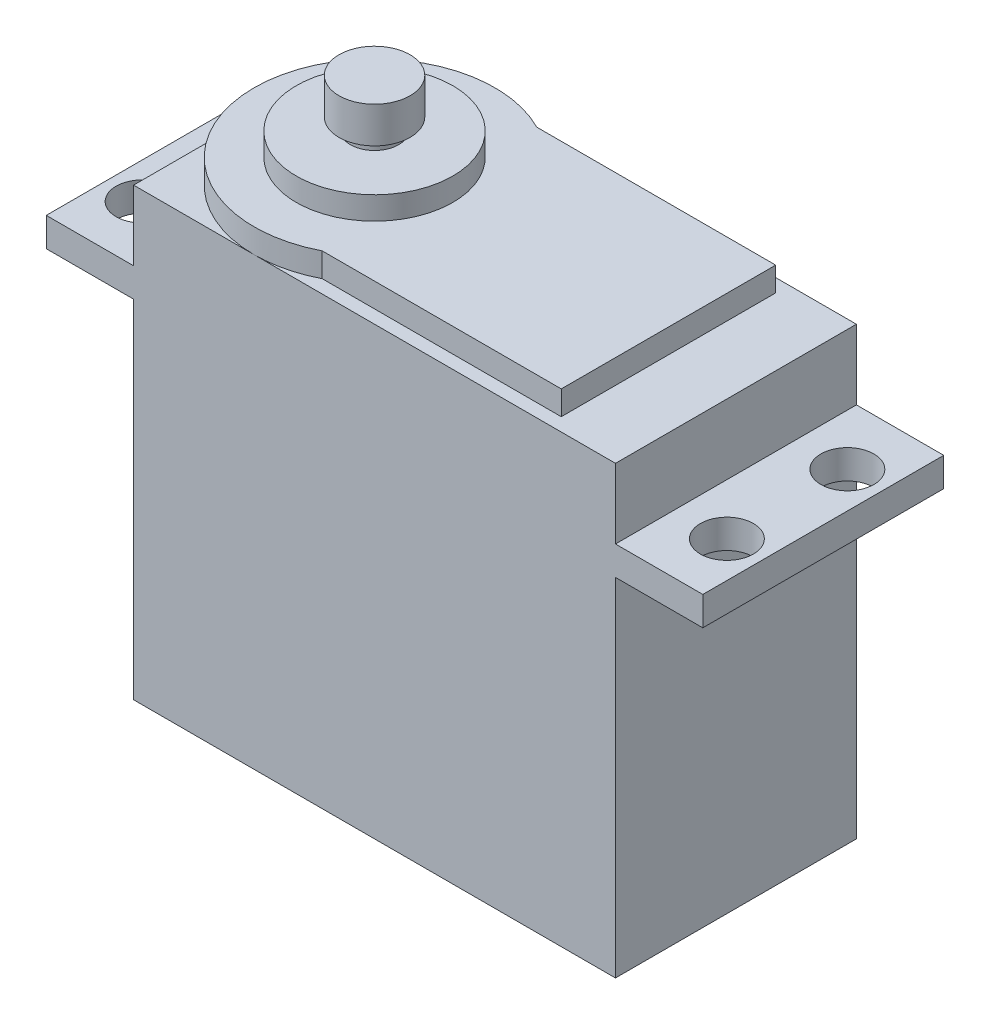
SolidWorks part; units mm, degrees
ref_plane "前视基准面" through (0, 0, 0) normal (0, 0, 1) x (1, 0, 0)
ref_plane "上视基准面" through (0, 0, 0) normal (0, 1, 0) x (1, 0, 0)
ref_plane "右视基准面" through (0, 0, 0) normal (1, 0, 0) x (0, 0, -1)
other "Configuration Table"
sketch "草图1" plane through (0, 0, 0) normal (0, 1, 0) x (1, 0, 0)
  line L1 (-20, 10) -> (20, 10)
  line L2 (-20, 10) -> (-20, -10)
  line L3 (-20, -10) -> (20, -10)
  line L4 (20, 10) -> (20, -10)
  line L5 (-20, 10) -> (20, -10) construction
  line L6 (-20, -10) -> (20, 10) construction
  point P0 (0, 0)
  dimension "D1" = 40
  dimension "D2" = 20
extrude "凸台-拉伸1" add sketch "草图1" along normal blind 37
sketch "草图2" plane through (0, 37, 0) normal (0, 1, 0) x (1, 0, 0)
  line L0 (0, 0) -> (0, 18.6395) construction
  line L1 (20, 10) -> (-20, 10) construction
  line L2 (-27.25, 10) -> (27.25, 10)
  line L3 (-27.25, 10) -> (-27.25, -10)
  line L4 (-27.25, -10) -> (27.25, -10)
  line L5 (27.25, 10) -> (27.25, -10)
  line L6 (-20, -10) -> (20, -10) construction
  line L7 (0, 0) -> (35.0108, 0) construction
  circle A0 centre (24.25, 5) radius 2.2
  circle A1 centre (24.25, -5) radius 2.2
  circle A2 centre (-24.25, 5) radius 2.2
  circle A3 centre (-24.25, -5) radius 2.2
  dimension "D2" = 4.4
  dimension "D3" = 48.5
  dimension "D4" = 10
  dimension "D1" = 54.5
extrude "凸台-拉伸2" add sketch "草图2" against normal blind 2.4 from offset 5.8 offset against normal yes
sketch "草图3" plane through (0, 37, 0) normal (0, 1, 0) x (1, 0, 0)
  line L0 (-18.731, 0) -> (35.4551, 0) construction
  line L1 (-20, 10) -> (-20, -10) construction
  line L2 (-20, -10) -> (20, -10) construction
  line L3 (-5.4404, 8.9) -> (14.4, 8.9)
  line L4 (14.4, 8.9) -> (14.4, -8.9)
  line L5 (14.4, -8.9) -> (-5.4404, -8.9)
  line L6 (20, -10) -> (20, 10) construction
  arc A0 (-5.4404, 8.9) -> (-5.4404, -8.9) centre (-10, 0) ccw
  dimension "D1" = 17.8
  dimension "D2" = 5.6
extrude "凸台-拉伸3" add sketch "草图3" along normal blind 2
sketch "草图4" plane through (0, 39, 0) normal (0, 1, 0) x (1, 0, 0)
  circle A0 centre (-10, 0) radius 6.5
  dimension "D1" = 13
extrude "凸台-拉伸4" add sketch "草图4" along normal blind 1.9
sketch "草图5" plane through (0, 40.9, 0) normal (0, 1, 0) x (1, 0, 0)
  circle A0 centre (-10, 0) radius 2
  dimension "D1" = 4
extrude "凸台-拉伸5" add sketch "草图5" along normal blind 4
sketch "草图6" plane through (0, 44.9, 0) normal (0, 1, 0) x (1, 0, 0)
  circle A1 centre (-10, 0) radius 2.95
  dimension "D1" = 5.9
extrude "凸台-拉伸6" add sketch "草图6" against normal blind 3
